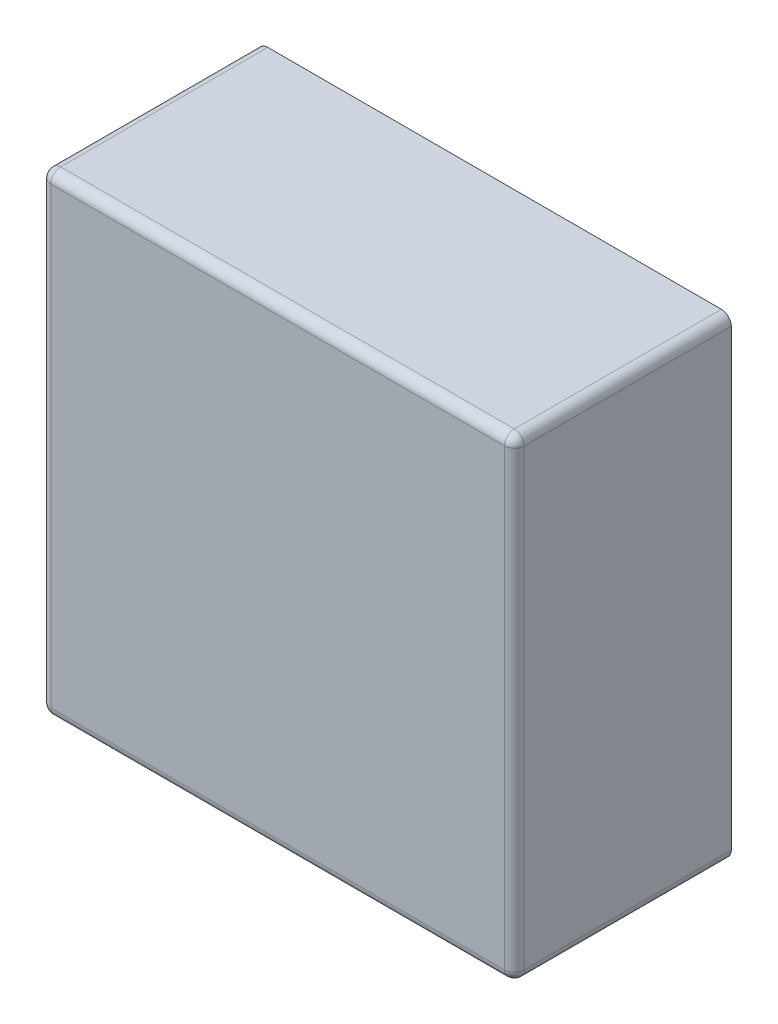
SolidWorks part; units mm, degrees
ref_plane "Plan de face" through (0, 0, 0) normal (0, 0, 1) x (1, 0, 0)
ref_plane "Plan de dessus" through (0, 0, 0) normal (0, 1, 0) x (1, 0, 0)
ref_plane "Plan de droite" through (0, 0, 0) normal (1, 0, 0) x (0, 0, -1)
ref_plane "Plan1" through (0, -2.15, 0) normal (0, -1, 0) x (1, 0, 0)
sketch "Esquisse1" plane through (0, -2.15, 0) normal (0, -1, 0) x (1, 0, 0)
  line L0 (1.9, 0.4) -> (2.8, 0.4)
  line L1 (2.8, 0.4) -> (2.8, 5.5)
  line L2 (2.8, 5.5) -> (-2.8, 5.5)
  line L3 (-2.8, 5.5) -> (-2.8, 0.4)
  line L4 (-2.8, 0.4) -> (-1.9, 0.4)
  line L5 (-1.9, 1) -> (-1.9, 3.1)
  line L6 (-1.9, 3.1) -> (1.9, 3.1)
  line L7 (1.9, 3.1) -> (1.9, 1)
  arc A0 (1.9, 1) -> (1.9, 0.4) centre (2.06, 0.7) ccw
  arc A1 (-1.9, 0.4) -> (-1.9, 1) centre (-2.06, 0.7) ccw
extrude "Boss.-Extru.1" add sketch "Esquisse1" against normal blind 4.3
sketch "Esquisse2" plane through (0, -2.15, 0) normal (0, -1, 0) x (1, 0, 0)
  line L0 (-2.8, 3.1) -> (-2.8, 5.5)
  line L1 (-2.8, 5.5) -> (2.8, 5.5)
  line L2 (2.8, 5.5) -> (2.8, 3.1)
  line L3 (2.8, 3.1) -> (-2.8, 3.1)
extrude "Boss.-Extru.2" add sketch "Esquisse2" along normal blind 0.65
sketch "Esquisse3" plane through (-2.8, 0, 0) normal (-1, 0, 0) x (0, 0, 1)
  line L0 (5.5, 2.15) -> (5.5, -2.8)
  line L1 (5.5, -2.8) -> (3.1, -2.8)
  line L2 (3.1, -2.8) -> (3.1, 2.15)
  line L3 (3.1, 2.15) -> (5.5, 2.15)
extrude "Boss.-Extru.3" add sketch "Esquisse3" along normal blind 2.4
sketch "Esquisse4" plane through (0, 2.15, 0) normal (0, 1, 0) x (-1, 0, 0)
  line L0 (-2.8, 5.5) -> (5.2, 5.5)
  line L1 (5.2, 5.5) -> (5.2, 3.1)
  line L2 (5.2, 3.1) -> (-2.8, 3.1)
  line L3 (-2.8, 3.1) -> (-2.8, 5.5)
extrude "Boss.-Extru.4" add sketch "Esquisse4" along normal blind 3.85
sketch "Esquisse5" plane through (2.8, 0, 0) normal (1, 0, 0) x (0, 0, -1)
  line L0 (-3.1, -2.8) -> (-5.5, -2.8)
  line L1 (-5.5, -2.8) -> (-5.5, 6)
  line L2 (-5.5, 6) -> (-3.1, 6)
  line L3 (-3.1, 6) -> (-3.1, -2.8)
extrude "Boss.-Extru.5" add sketch "Esquisse5" along normal blind 3.2
sketch "Esquisse6" plane through (0, 0, 3.1) normal (0, 0, -1) x (-1, 0, 0)
  line L0 (5.2, 5.2) -> (0.475, 5.2)
  line L1 (0.475, 5.2) -> (0.475, 2.8)
  line L2 (0.475, 2.8) -> (1.175, 2.8)
  line L3 (1.175, 2.8) -> (1.175, 1.9)
  line L4 (1.175, 1.9) -> (-1.175, 1.9)
  line L5 (-1.175, 1.9) -> (-1.175, 2.8)
  line L6 (-1.175, 2.8) -> (-0.475, 2.8)
  line L7 (-0.475, 2.8) -> (-0.475, 5.2)
  line L8 (-0.475, 5.2) -> (-5.2, 5.2)
  line L9 (-5.2, 5.2) -> (-5.2, -2.8)
  line L10 (-5.2, -2.8) -> (-6, -2.8)
  line L11 (-6, -2.8) -> (-6, 6)
  line L12 (-6, 6) -> (5.2, 6)
  line L13 (5.2, 6) -> (5.2, 5.2)
  line L14 (-1.175, -2.8) -> (-1.175, -1.9)
  line L15 (-1.175, -1.9) -> (1.175, -1.9)
  line L16 (1.175, -1.9) -> (1.175, -2.8)
  line L17 (1.175, -2.8) -> (-1.175, -2.8)
extrude "Boss.-Extru.6" add sketch "Esquisse6" along normal blind 3.1
sketch "Esquisse7" plane through (0, 0, 0.4) normal (0, 0, -1) x (-1, 0, 0)
  line L0 (1.9, -2.15) -> (1.9, 2.15)
  line L1 (1.9, 2.15) -> (2.8, 2.15)
  line L2 (2.8, 2.15) -> (2.8, -2.15)
  line L3 (2.8, -2.15) -> (1.9, -2.15)
extrude "Boss.-Extru.7" add sketch "Esquisse7" along normal blind 0.4
sketch "Esquisse8" plane through (0, 0, 0.4) normal (0, 0, -1) x (-1, 0, 0)
  line L0 (-1.9, -2.15) -> (-2.8, -2.15)
  line L1 (-2.8, -2.15) -> (-2.8, 2.15)
  line L2 (-2.8, 2.15) -> (-1.9, 2.15)
  line L3 (-1.9, 2.15) -> (-1.9, -2.15)
extrude "Boss.-Extru.8" add sketch "Esquisse8" along normal blind 0.4
sketch "Esquisse9" plane through (-5.2, 0, 0) normal (-1, 0, 0) x (0, 0, 1)
  line L0 (0, -2.8) -> (0, 6)
  line L1 (0, 6) -> (5.5, 6)
  line L2 (5.5, 6) -> (5.5, -2.8)
  line L3 (5.5, -2.8) -> (0, -2.8)
extrude "Boss.-Extru.9" add sketch "Esquisse9" along normal blind 0.8
sketch "Esquisse10" plane through (0, -2.8, 0) normal (0, -1, 0) x (1, 0, 0)
  line L0 (-0.475, 3.1) -> (-5.2, 3.1)
  line L1 (-5.2, 3.1) -> (-5.2, 0)
  line L2 (-5.2, 0) -> (-6, 0)
  line L3 (-6, 0) -> (-6, 5.5)
  line L4 (-6, 5.5) -> (6, 5.5)
  line L5 (6, 5.5) -> (6, 0)
  line L6 (6, 0) -> (5.2, 0)
  line L7 (5.2, 0) -> (5.2, 3.1)
  line L8 (5.2, 3.1) -> (0.475, 3.1)
  line L9 (0.475, 3.1) -> (0.475, 0)
  line L10 (0.475, 0) -> (-0.475, 0)
  line L11 (-0.475, 0) -> (-0.475, 3.1)
extrude "Boss.-Extru.10" add sketch "Esquisse10" along normal blind 2.4
sketch "Esquisse11" plane through (0, -5.2, 0) normal (0, -1, 0) x (1, 0, 0)
  line L0 (-6, 0) -> (-6, 5.5)
  line L1 (-6, 5.5) -> (6, 5.5)
  line L2 (6, 5.5) -> (6, 0)
  line L3 (6, 0) -> (-6, 0)
extrude "Boss.-Extru.11" add sketch "Esquisse11" along normal blind 0.8
sketch "Esquisse12" plane through (0, 0, 3.1) normal (0, 0, -1) x (-1, 0, 0)
  line L0 (-1.9, 0.475) -> (-1.175, 0.475)
  line L1 (-1.175, 0.475) -> (-1.175, 2.8)
  line L2 (-1.175, 2.8) -> (-0.475, 2.8)
  line L3 (-0.475, 2.8) -> (-0.475, 5.2)
  line L4 (-0.475, 5.2) -> (-5.2, 5.2)
  line L5 (-5.2, 5.2) -> (-5.2, -5.2)
  line L6 (-5.2, -5.2) -> (-0.475, -5.2)
  line L7 (-0.475, -5.2) -> (-0.475, -2.8)
  line L8 (-0.475, -2.8) -> (-1.175, -2.8)
  line L9 (-1.175, -2.8) -> (-1.175, -0.475)
  line L10 (-1.175, -0.475) -> (-1.9, -0.475)
  line L11 (-1.9, -0.475) -> (-1.9, -2.15)
  line L12 (-1.9, -2.15) -> (-2.8, -2.15)
  line L13 (-2.8, -2.15) -> (-2.8, 2.15)
  line L14 (-2.8, 2.15) -> (-1.9, 2.15)
  line L15 (-1.9, 2.15) -> (-1.9, 0.475)
extrude "Enlèv. mat.-Extru.1" cut sketch "Esquisse12" against normal blind 1.6
ref_plane "Plan2" through (0.475, 0, 0) normal (-1, 0, 0) x (0, -1, 0)
sketch "Esquisse13" plane through (0.475, 0, 0) normal (-1, 0, 0) x (0, -1, 0)
  line L0 (-1.9, 3.1) -> (-0.475, 3.1)
  line L1 (-0.475, 3.1) -> (-0.475, 4.7)
  line L2 (-0.475, 4.7) -> (-1.9, 4.7)
  line L3 (-1.9, 4.7) -> (-1.9, 3.1)
extrude "Enlèv. mat.-Extru.2" cut sketch "Esquisse13" against normal up to next
sketch "Esquisse14" plane through (0.475, 0, 0) normal (-1, 0, 0) x (0, -1, 0)
  line L0 (0.475, 3.1) -> (1.9, 3.1)
  line L1 (1.9, 3.1) -> (1.9, 4.7)
  line L2 (1.9, 4.7) -> (0.475, 4.7)
  line L3 (0.475, 4.7) -> (0.475, 3.1)
extrude "Enlèv. mat.-Extru.3" cut sketch "Esquisse14" against normal up to next
sketch "Esquisse15" plane through (0, 0, 3.1) normal (0, 0, -1) x (-1, 0, 0)
  line L0 (0.475, 0.475) -> (1.9, 0.475)
  line L1 (1.9, 0.475) -> (1.9, 2.15)
  line L2 (1.9, 2.15) -> (2.8, 2.15)
  line L3 (2.8, 2.15) -> (2.8, -2.15)
  line L4 (2.8, -2.15) -> (1.9, -2.15)
  line L5 (1.9, -2.15) -> (1.9, -0.475)
  line L6 (1.9, -0.475) -> (0.475, -0.475)
  line L7 (0.475, -0.475) -> (0.475, -1.9)
  line L8 (0.475, -1.9) -> (1.175, -1.9)
  line L9 (1.175, -1.9) -> (1.175, -2.8)
  line L10 (1.175, -2.8) -> (0.475, -2.8)
  line L11 (0.475, -2.8) -> (0.475, -5.2)
  line L12 (0.475, -5.2) -> (5.2, -5.2)
  line L13 (5.2, -5.2) -> (5.2, 5.2)
  line L14 (5.2, 5.2) -> (0.475, 5.2)
  line L15 (0.475, 5.2) -> (0.475, 2.8)
  line L16 (0.475, 2.8) -> (1.175, 2.8)
  line L17 (1.175, 2.8) -> (1.175, 1.9)
  line L18 (1.175, 1.9) -> (0.475, 1.9)
  line L19 (0.475, 1.9) -> (0.475, 0.475)
extrude "Enlèv. mat.-Extru.4" cut sketch "Esquisse15" against normal blind 1.6
fillet "Congé1" radius 0.25 8 edges at (6, 6, 2.75) (-6, 6, 2.75) (0, -6, 5.5) (0, 6, 5.5) (-6, 0, 5.5) (6, 0, 5.5) (6, -6, 2.75) (-6, -6, 2.75)
